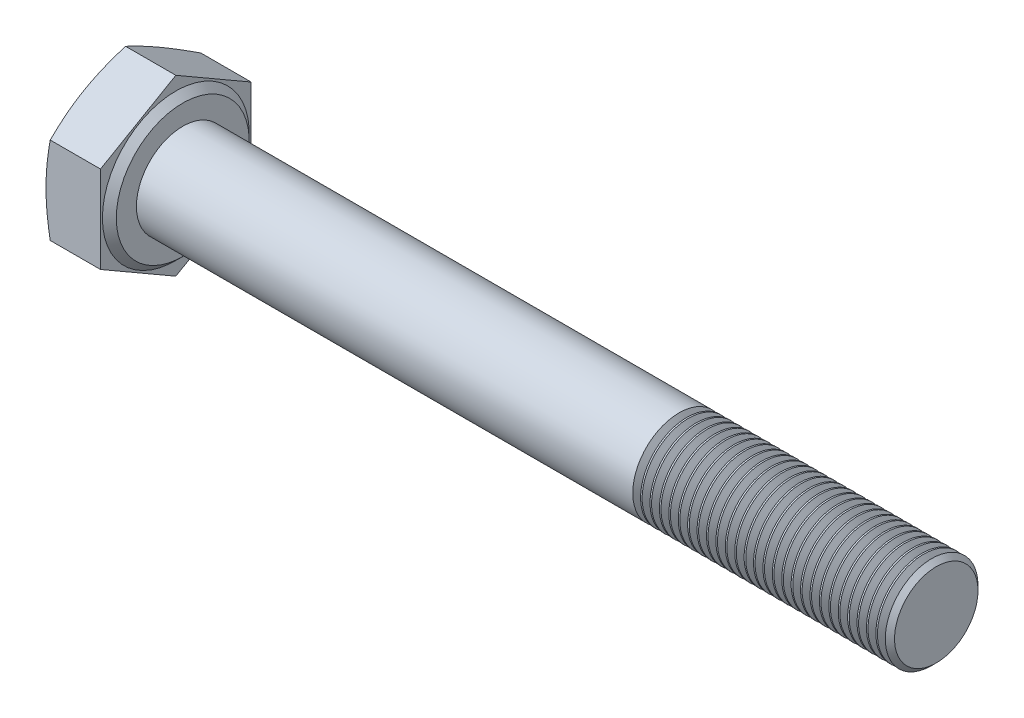
SolidWorks part; units mm, degrees
ref_plane "Front" through (0, 0, 0) normal (0, 0, 1) x (1, 0, 0)
ref_plane "Top" through (0, 0, 0) normal (0, 1, 0) x (1, 0, 0)
ref_plane "Right" through (0, 0, 0) normal (1, 0, 0) x (0, 0, -1)
sketch "Sketch2" plane through (0, 0, 0) normal (1, 0, 0) x (0, 0, -1)
  line L1 (0, -7.5056) -> (6.5, -3.7528)
  line L2 (6.5, -3.7528) -> (6.5, 3.7528)
  line L3 (6.5, 3.7528) -> (0, 7.5056)
  line L4 (0, 7.5056) -> (-6.5, 3.7528)
  line L5 (-6.5, 3.7528) -> (-6.5, -3.7528)
  line L6 (-6.5, -3.7528) -> (0, -7.5056)
  circle A0 centre (0, 0) radius 6.5 construction
  dimension "s" = 13
extrude "BaseHead" add sketch "Sketch2" along normal blind 5.3
sketch "Sketch3" plane through (0, 0, 0) normal (0, 0, 1) x (1, 0, 0)
  line L0 (5.3, 7.5056) -> (5.3, 5.735)
  line L2 (5.3, 5.735) -> (4.7, 6.335)
  line L3 (4.7, 6.335) -> (4.7, 7.5056)
  line L5 (4.7, 7.5056) -> (5.3, 7.5056)
  line L6 (-0.9571, 0) -> (7.6478, 0) construction
  line L7 (5.3, 7.5056) -> (0, 7.5056) construction
  dimension "D1" = 45
  dimension "c" = 0.6
  dimension "dw" = 11.47
revolve "BearingFace" cut sketch "Sketch3" angle 360 about L6
sketch "Sketch4" plane through (0, 0, 0) normal (0, 0, 1) x (1, 0, 0)
  line L0 (-0.4935, 0) -> (3.5626, 0) construction
  line L2 (0, 7.5056) -> (0.366, 7.5056)
  line L4 (0.366, 7.5056) -> (0, 6.5)
  line L6 (0, 6.5) -> (0, 7.5056)
  line L7 (4.7, 7.5056) -> (0, 7.5056) construction
  dimension "D1" = 20
  dimension "D2" = 13
revolve "HeadChamfer" cut sketch "Sketch4" angle 360 about L0
ref_plane "Plane1" through (48.3, 0, 0) normal (1, 0, 0) x (0, 0, -1)
sketch "Sketch5" plane through (5.3, 0, 0) normal (1, 0, 0) x (0, 0, -1)
  circle A0 centre (0, 0) radius 4
  dimension "d" = 8
extrude "BaseBody" add sketch "Sketch5" along normal blind 65
cosmetic thread "ThreadCosmetic1" [suppressed] parameters "D1"=22, "D2"=6.647
chamfer "Chamfer1" distance 0.4 angle 45 1 edges at (70.3, 0, -4)
fillet "HeadFillet" [suppressed] radius 0.4
sketch "Sketch6" plane through (0, 0, 0) normal (0, 0, 1) x (1, 0, 0)
  line L0 (69.2235, 4.6765) -> (69.9, 4.6765)
  line L1 (69.9, 4.6765) -> (69.9, 4)
  line L2 (69.9, 4) -> (69.5618, 3.4141)
  line L3 (69.5618, 3.4141) -> (69.2235, 4)
  line L4 (69.2235, 4) -> (69.2235, 4.6765)
  line L5 (69.9, -4) -> (69.9, 4) construction
  line L6 (69.9, 4) -> (5.3, 4) construction
  dimension "D1" = 0.6765
revolve "Cut-Revolve10" cut sketch "Sketch6" angle 360 about axis through (70.3, 0, 0) along (-1, 0, 0)
pattern_linear "LPattern10" count 27 spacing 0.8118 along (-1, 0, 0) of "Cut-Revolve10"
equation "\"D2@Sketch4\" = \"s@Sketch2\""
equation "\"D1@Chamfer1\" = 0.05 * \"d@Sketch5\""
equation "\"D1@ThreadCosmetic1\" = \"l@BaseBody\" - \"lg@Plane1\""
equation "\"D1@Sketch6\" =  ( \"d@Sketch5\" - \"D2@ThreadCosmetic1\" )  / 2"
equation "\"pitch@LPattern10\" = 1.2 * \"D1@Sketch6\""
equation "\"D1@LPattern10\" = \"D1@ThreadCosmetic1\" / \"pitch@LPattern10\""
